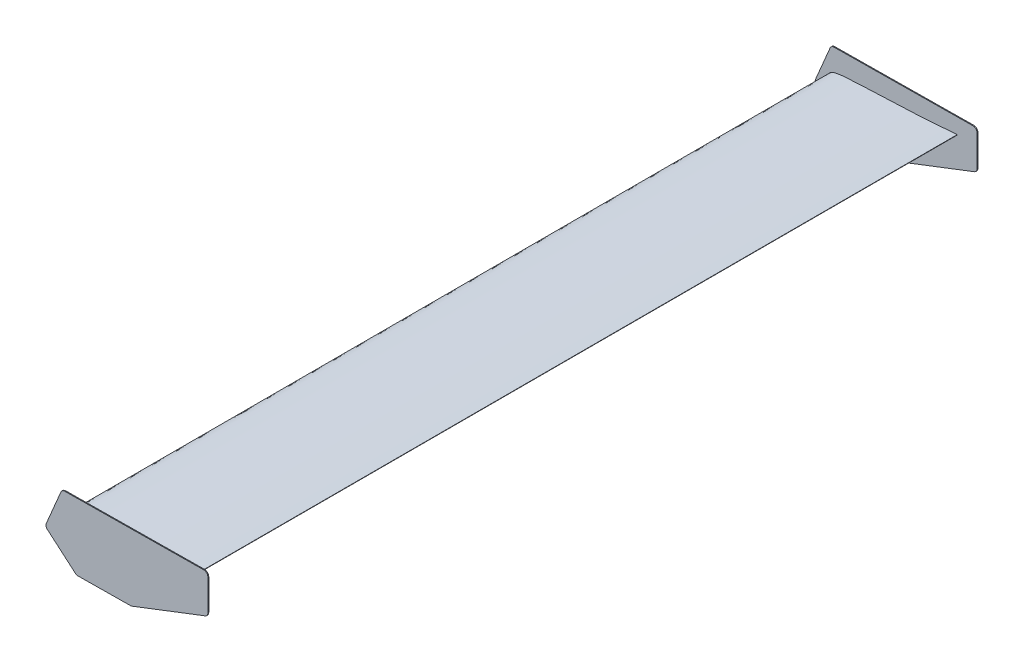
SolidWorks part; units mm, degrees
ref_plane "Front Plane" through (0, 0, 0) normal (0, 0, 1) x (1, 0, 0)
ref_plane "Top Plane" through (0, 0, 0) normal (0, 1, 0) x (1, 0, 0)
ref_plane "Right Plane" through (0, 0, 0) normal (1, 0, 0) x (0, 0, -1)
curve "Airfoil Curve"
  spline degree 3 poles (300, -0.39, 0) (295.0052, -1.7497, 0) (285.0396, -4.4626, 0) (265.0756, -9.3952, 0) (240.11, -14.8452, 0) (210.0811, -20.2176, 0) (180.0755, -24.6212, 0) (150.0532, -27.7624, 0) (120.0335, -29.7214, 0) (94.9726, -29.7413, 0) (74.963, -28.3569, 0) (59.9355, -26.5335, 0) (44.8755, -23.8445, 0) (32.3958, -20.6106, 0) (22.3952, -17.3445, 0) (14.8545, -14.2611, 0) (8.4203, -10.9265, 0) (2.8355, -6.9378, 0) (-2.0261, -0.5226, 0) (3.2214, 4.3836, 0) (8.5759, 6.3095, 0) (14.9528, 7.6093, 0) (22.4839, 8.2702, 0) (32.4958, 8.738, 0) (45.0031, 8.7029, 0) (60.0065, 8.2831, 0) (74.9993, 7.4837, 0) (94.9994, 6.5483, 0) (119.9952, 5.3479, 0) (150.0009, 4.2208, 0) (179.9969, 2.9692, 0) (209.9958, 1.9031, 0) (239.9971, 1.119, 0) (264.9992, 0.7209, 0) (284.9995, 0.4587, 0) (294.9999, 0.4129, 0) (300, 0.39, 0) knots 0 0 0 0 0.025305 0.050488 0.10052 0.150191 0.199587 0.24874 0.297716 0.346601 0.371103 0.395726 0.42057 0.445825 0.458702 0.47192 0.485786 0.493461 0.506863 0.516148 0.522766 0.535269 0.547551 0.559786 0.584229 0.608681 0.633151 0.657622 0.706558 0.755482 0.804406 0.85332 0.902221 0.951113 0.975557 1 1 1 1
ref_plane "Plane1" through (300, -0.39, 0) normal (-0.9649, -0.2627, 0) x (0, 0, 1)
sketch "AirfoilSketch" plane through (0, 0, 0) normal (0, 0, 1) x (1, 0, 0)
  line L2 (0, 0) -> (350.3559, 0) construction
  line B0 (298.8587, 26.1467) -> (298.9256, 25.3696)
  line B1 (0, 0) -> (298.8587, 26.1467) construction
  spline B2 degree 3 poles (298.9256, 25.3696) (294.066, 23.5861) (284.3701, 20.0276) (264.9034, 13.399) (240.4979, 5.8256) (211.0412, -2.1052) (181.5245, -9.0689) (151.8827, -14.7762) (122.1421, -19.3055) (97.1755, -21.477) (77.1209, -21.8158) (61.9923, -21.2894) (46.7571, -19.9034) (34.0458, -17.7529) (23.8017, -15.3575) (16.0241, -12.933) (9.3274, -10.1632) (3.4207, -6.6687) (-1.9738, -0.6946) (2.8331, 4.644) (8.0025, 7.0225) (14.2443, 8.8651) (21.6908, 10.1702) (31.6256, 11.4958) (44.0897, 12.5348) (59.0737, 13.4047) (74.0798, 13.8955) (94.0863, 14.6808) (119.0929, 15.631) (149.0845, 17.0844) (179.0772, 18.4129) (209.0569, 19.9265) (239.0147, 21.7212) (263.9588, 23.4712) (283.9077, 24.9272) (293.8751, 25.7402) (298.8587, 26.1467) knots 0 0 0 0 0.025305 0.050488 0.10052 0.150191 0.199587 0.24874 0.297716 0.346601 0.371103 0.395726 0.42057 0.445825 0.458702 0.47192 0.485786 0.493461 0.506863 0.516148 0.522766 0.535269 0.547551 0.559786 0.584229 0.608681 0.633151 0.657622 0.706558 0.755482 0.804406 0.85332 0.902221 0.951113 0.975557 1 1 1 1
  dimension "AoA_Rear_Wing" = 5
sketch_block_instance "AirfoilBlock-1"
sketch_block "AirfoilBlock"
extrude "Rear Wing" add sketch "AirfoilSketch" along normal mid plane 1800
sketch "Endplate Sketch" plane through (0, 0, 900) normal (0, 0, 1) x (1, 0, 0)
  line L0 (4.1984, 59.4067) -> (-35.2909, -33.8505)
  line L1 (-35.2909, -33.8505) -> (38.2575, -96.7338)
  line L2 (4.1984, 59.4067) -> (345.6673, 62.9082)
  line L3 (345.6673, 62.9082) -> (345.6673, -26.3186)
  line L5 (38.2575, -96.7338) -> (166.2751, -95.4211)
  line L6 (166.2751, -95.4211) -> (345.6673, -26.3186)
  point P2 (152.1224, -101.9226)
  point P6 (313.3454, 63.1358)
  point P7 (345.6673, -26.3186)
  point P8 (345.6673, 62.9082)
  point P9 (4.1984, 59.4067)
  point P10 (-35.2909, -33.8505)
extrude "Endplate" add sketch "Endplate Sketch" along normal mid plane 2
fillet "Endplate Fillet" radius 10 6 edges at (345.6673, 62.9082, 900) (345.6673, -26.3186, 900) (166.2751, -95.4211, 900) (4.1984, 59.4067, 900) (-35.2909, -33.8505, 900) (38.2575, -96.7338, 900)
mirror "Mirror3" about plane through (0, 0, 0) normal (0, 0, 1) of "Endplate Fillet", "Endplate"
